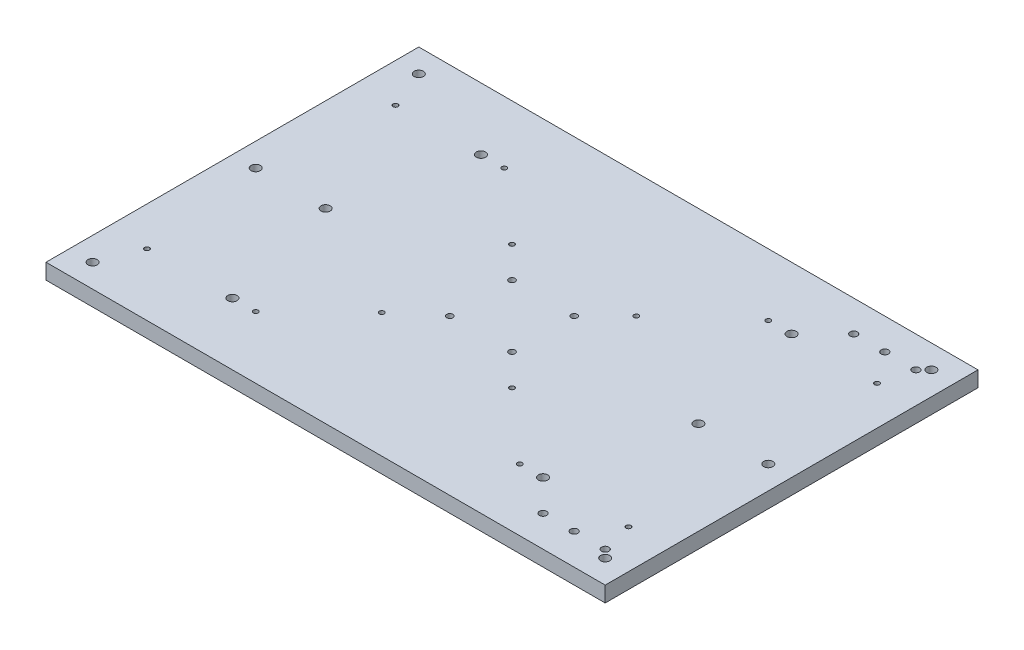
SolidWorks part; units mm, degrees
ref_plane "Front Plane" through (0, 0, 0) normal (0, 0, 1) x (1, 0, 0)
ref_plane "Top Plane" through (0, 0, 0) normal (0, 1, 0) x (1, 0, 0)
ref_plane "Right Plane" through (0, 0, 0) normal (1, 0, 0) x (0, 0, -1)
sketch "Sketch1" plane through (0, 0, 0) normal (0, 1, 0) x (1, 0, 0)
  line L1 (-457.2, 304.8) -> (457.2, 304.8)
  line L2 (-457.2, 304.8) -> (-457.2, -304.8)
  line L3 (-457.2, -304.8) -> (457.2, -304.8)
  line L4 (457.2, 304.8) -> (457.2, -304.8)
  line L5 (-457.2, 304.8) -> (457.2, -304.8) construction
  line L6 (-457.2, -304.8) -> (457.2, 304.8) construction
  point P0 (0, 0)
  dimension "D1" = 914.4
  dimension "D2" = 609.6
extrude "Boss-Extrude1" add sketch "Sketch1" along normal mid plane 25.4
hole_wizard "9/16 Clearance Hole1" positions "Sketch3" profile "Sketch2" hole size "9/16" standard "ANSI Inch" end condition up to next
sketch "Sketch3" plane through (0, 12.7, 0) normal (0, 1, 0) x (1, 0, 0)
  line L0 (457.2, -304.8) -> (457.2, 304.8) construction
  line L1 (-457.2, 304.8) -> (-457.2, -304.8) construction
  line L2 (457.2, 304.8) -> (-457.2, 304.8) construction
  line L3 (-457.2, -304.8) -> (457.2, -304.8) construction
  point P0 (419.1, 0)
  point P2 (-419.1, 266.7)
  point P4 (-419.1, -266.7)
  point P15 (-254, 203.2)
  point P17 (-254, -203.2)
  point P19 (304.8, 0)
  dimension "D1" = 38.1
  dimension "D2" = 38.1
  dimension "D3" = 38.1
  dimension "D4" = 38.1
  dimension "D5" = 101.6
  dimension "D6" = 203.2
  dimension "D7" = 101.6
  dimension "D8" = 203.2
  dimension "D9" = 152.4
sketch "Sketch2" plane through (419.1, 12.7, 0) normal (1, 0, 0) x (0, 0, 1)
  line L0 (0, 0) -> (0, 25.401)
  line L1 (0, 25.401) -> (7.54, 25.401)
  line L2 (7.54, 25.401) -> (7.54, 0)
  line L5 (7.54, 0) -> (0, 0)
  line L11 (0, -6.35) -> (0, 107.95) construction
  dimension "Thru Hole Dia." = 15.08
  dimension "Thru Hole Depth" = 25.401
sketch "Sketch5" plane through (0, -12.7, 0) normal (0, -1, 0) x (1, 0, 0)
  circle A0 centre (161.29, 279.4) radius 5.08
  circle A1 centre (161.29, -279.4) radius 5.08
  circle A2 centre (-322.58, 0) radius 5.08
  dimension "D1" = 161.29
  dimension "D2" = 322.58
  dimension "D3" = 279.4
  dimension "D4" = 279.4
extrude "Cut-Extrude1" cut sketch "Sketch5" against normal blind 2.54
hole_wizard "CBORE for 3/8 Socket Head Cap Screw1" positions "Sketch7" profile "Sketch6" counterbore size "3/8" standard "ANSI Inch" end condition up to next
sketch "Sketch7" plane through (0, -12.7, 0) normal (0, -1, 0) x (-1, 0, 0)
  point P0 (50.8, -50.8)
  point P2 (-50.8, -50.8)
  point P4 (-50.8, 50.8)
  point P6 (50.8, 50.8)
  dimension "D1" = 50.8
  dimension "D2" = 50.8
  dimension "D3" = 50.8
  dimension "D4" = 50.8
sketch "Sketch6" plane through (-50.8, -12.7, 50.8) normal (1, 0, 0) x (0, 0, -1)
  line L0 (0, 0) -> (0, 25.4)
  line L1 (0, 25.4) -> (5.0419, 25.4)
  line L3 (5.0419, 25.4) -> (5.0419, 9.525)
  line L4 (5.0419, 9.525) -> (7.9375, 9.525)
  line L5 (7.9375, 9.525) -> (7.9375, 0)
  line L7 (7.9375, 0) -> (0, 0)
  line L11 (0, -6.35) -> (0, 107.95) construction
  dimension "Thru Hole Dia." = 10.0838
  dimension "Thru Hole Depth" = 25.4
  dimension "C'Bore Dia." = 15.875
  dimension "C'Bore Depth" = 9.525
hole_wizard "3/8-16 Tapped Hole1" positions "Sketch9" profile "Sketch8" tap size "3/8-16" standard "ANSI Inch" end condition up to next
sketch "Sketch9" plane through (0, 12.7, 0) normal (0, 1, 0) x (1, 0, 0)
  point P0 (-101.6, 101.6)
  point P2 (101.6, 101.6)
  point P4 (101.6, -101.6)
  point P6 (-111.3867, -101.6)
  dimension "D1" = 101.6
  dimension "D2" = 101.6
  dimension "D3" = 101.6
  dimension "D4" = 101.6
sketch "Sketch8" plane through (-101.6, 12.7, -101.6) normal (1, 0, 0) x (0, 0, 1)
  line L0 (0, 0) -> (0, 25.4)
  line L1 (0, 25.4) -> (3.9687, 25.4)
  line L2 (3.9687, 25.4) -> (3.9687, 0)
  line L5 (3.9687, 0) -> (0, 0)
  line L11 (0, -6.35) -> (0, 107.95) construction
  dimension "Thru Tap Drill Dia." = 7.9375
  dimension "Thru Tap Drill Depth" = 25.4
cosmetic thread "Hole Thread4" parameters "D2"=9.525
cosmetic thread "Hole Thread5" parameters "D2"=9.525
cosmetic thread "Hole Thread6" parameters "D2"=9.525
cosmetic thread "Hole Thread7" parameters "D2"=9.525
hole_wizard "3/8-16 Tapped Hole2" positions "Sketch11" profile "Sketch10" tap size "3/8-16" standard "ANSI Inch" end condition up to next
sketch "Sketch11" plane through (0, 12.7, 0) normal (0, 1, 0) x (1, 0, 0)
  line L0 (457.2, -304.8) -> (457.2, 304.8) construction
  line L1 (457.2, 304.8) -> (-457.2, 304.8) construction
  line L2 (-457.2, -304.8) -> (457.2, -304.8) construction
  point P0 (215.9, 203.2)
  point P2 (393.7, 203.2)
  point P4 (393.7, -203.2)
  point P6 (215.9, -203.2)
  dimension "D1" = 63.5
  dimension "D2" = 177.8
  dimension "D3" = 101.6
  dimension "D4" = 101.6
sketch "Sketch10" plane through (215.9, 12.7, -203.2) normal (1, 0, 0) x (0, 0, 1)
  line L0 (0, 0) -> (0, 25.401)
  line L1 (0, 25.401) -> (3.9687, 25.401)
  line L2 (3.9687, 25.401) -> (3.9687, 0)
  line L5 (3.9687, 0) -> (0, 0)
  line L11 (0, -6.35) -> (0, 107.95) construction
  dimension "Thru Tap Drill Dia." = 7.9375
  dimension "Thru Tap Drill Depth" = 25.401
cosmetic thread "Hole Thread8" parameters "D2"=9.525
cosmetic thread "Hole Thread9" parameters "D2"=9.525
cosmetic thread "Hole Thread10" parameters "D2"=9.525
cosmetic thread "Hole Thread11" parameters "D2"=9.525
mirror "Mirror1" about plane through (0, 0, 0) normal (1, 0, 0) of "3/8-16 Tapped Hole2"
mirror "Mirror2" about plane through (0, 0, 0) normal (1, 0, 0) of "9/16 Clearance Hole1"
hole_wizard "7/16 Clearance Hole1" positions "Sketch12" profile "Sketch13" hole size "7/16" standard "ANSI Inch" end condition through all
sketch "Sketch12" plane through (0, 12.7, 0) normal (0, 1, 0) x (1, 0, 0)
  line L0 (-457.2, -304.8) -> (457.2, -304.8) construction
  line L1 (457.2, -304.8) -> (457.2, 304.8) construction
  point P0 (406.4, -254)
  point P2 (355.6, -254)
  point P4 (304.8, -254)
  dimension "D1" = 50.8
  dimension "D2" = 50.8
  dimension "D3" = 50.8
  dimension "D4" = 50.8
  dimension "D5" = 50.8
  dimension "D6" = 50.8
sketch "Sketch13" plane through (406.4, 12.7, 254) normal (1, 0, 0) x (0, 0, 1)
  line L0 (0, 0) -> (0, 25.4)
  line L1 (0, 25.4) -> (5.9525, 25.4)
  line L2 (5.9525, 25.4) -> (5.9525, 0)
  line L5 (5.9525, 0) -> (0, 0)
  line L11 (0, -6.35) -> (0, 107.95) construction
  dimension "Thru Hole Dia." = 11.905
  dimension "Thru Hole Depth" = 25.4
mirror "Mirror3" about plane through (0, 0, 0) normal (0, 0, 1) of "7/16 Clearance Hole1"
